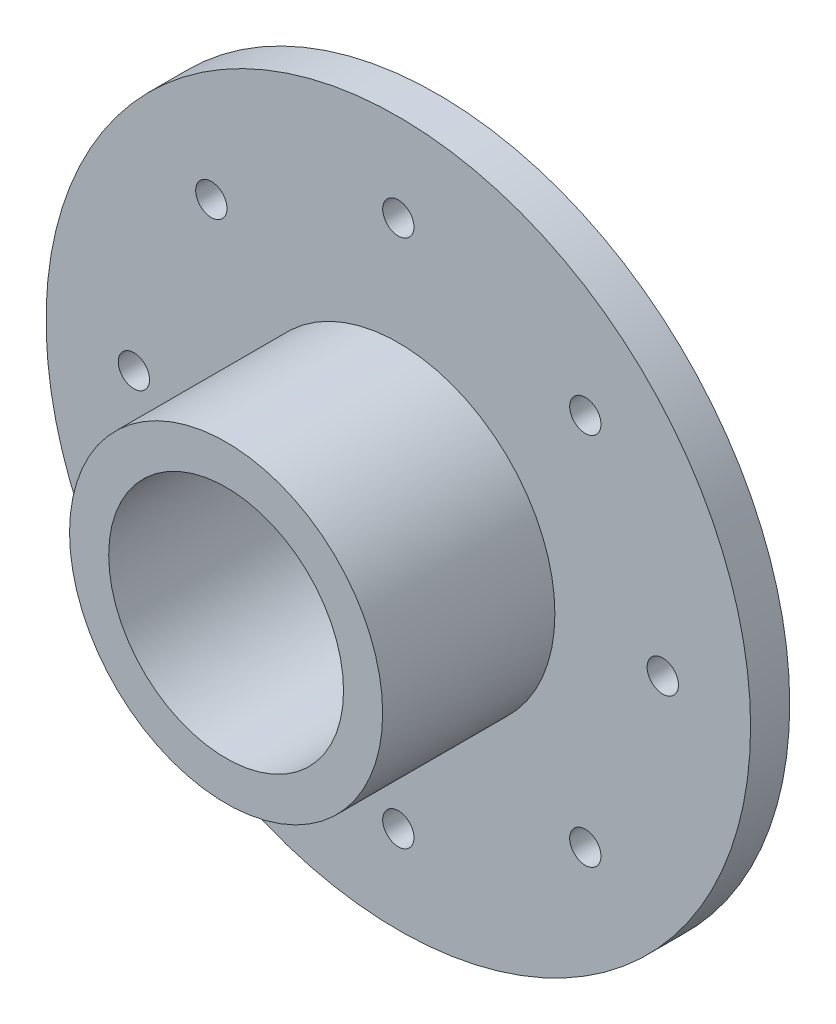
SolidWorks part; units mm, degrees
ref_plane "Спереди" through (0, 0, 0) normal (0, 0, 1) x (1, 0, 0)
ref_plane "Сверху" through (0, 0, 0) normal (0, 1, 0) x (1, 0, 0)
ref_plane "Справа" through (0, 0, 0) normal (1, 0, 0) x (0, 0, -1)
sketch "Эскиз1" plane through (0, 0, 0) normal (0, 0, 1) x (1, 0, 0)
  circle A1 centre (0, 0) radius 45
extrude "Вытянуть1" add sketch "Эскиз1" along normal blind 5
sketch "Эскиз2" plane through (0, 0, 5) normal (0, 0, 1) x (1, 0, 0)
  circle A0 centre (0, 0) radius 15
  circle A1 centre (0, 0) radius 20
extrude "Вытянуть2" add sketch "Эскиз2" along normal blind 22
sketch "Эскиз3" plane through (0, 0, 5) normal (0, 0, 1) x (1, 0, 0)
  circle A0 centre (0, 33.7812) radius 2
  circle A1 centre (23.8869, 23.8869) radius 2
  circle A2 centre (33.7812, 0) radius 2
  circle A3 centre (23.8869, -23.8869) radius 2
  circle A4 centre (0, -33.7812) radius 2
  circle A5 centre (-23.8869, -23.8869) radius 2
  circle A6 centre (-33.7812, 0) radius 2
  circle A7 centre (-23.8869, 23.8869) radius 2
extrude "Вытянуть3" cut sketch "Эскиз3" against normal through all
